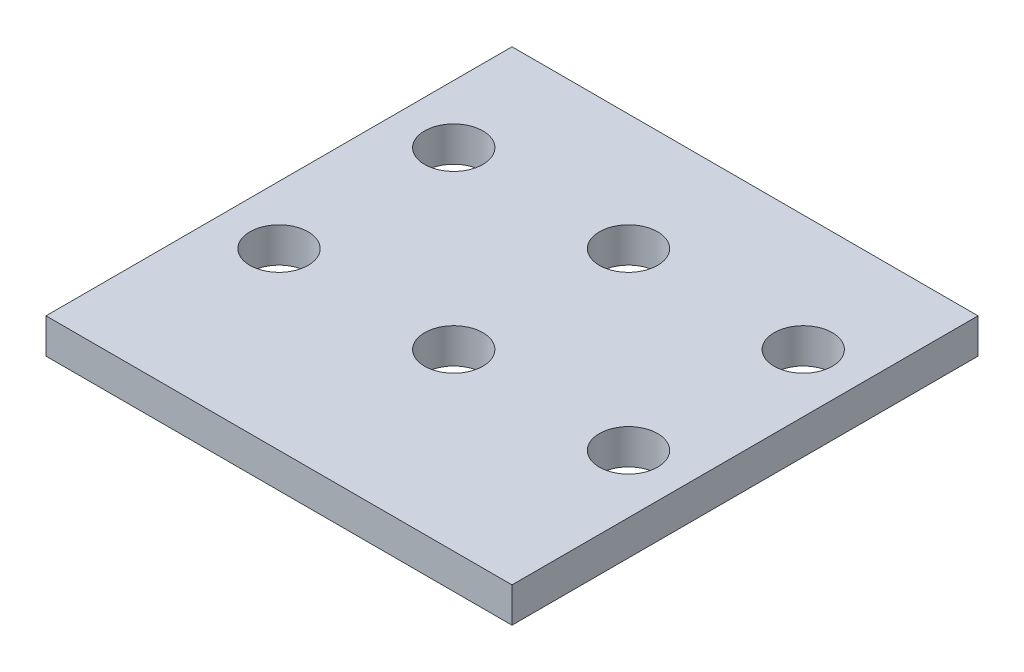
SolidWorks part; units mm, degrees
ref_plane "Front Plane" through (0, 0, 0) normal (0, 0, 1) x (1, 0, 0)
ref_plane "Top Plane" through (0, 0, 0) normal (0, 1, 0) x (1, 0, 0)
ref_plane "Right Plane" through (0, 0, 0) normal (1, 0, 0) x (0, 0, -1)
sketch "Sketch1" plane through (0, 0, 0) normal (0, 1, 0) x (1, 0, 0)
  line L1 (-25.4, -25.4) -> (25.4, -25.4)
  line L2 (-25.4, -25.4) -> (-25.4, 25.4)
  line L3 (-25.4, 25.4) -> (25.4, 25.4)
  line L4 (25.4, -25.4) -> (25.4, 25.4)
  line L5 (-25.4, -25.4) -> (25.4, 25.4) construction
  line L6 (-25.4, 25.4) -> (25.4, -25.4) construction
  point P0 (0, 0)
  dimension "D1" = 50.8
  dimension "D2" = 50.8
extrude "Boss-Extrude1" add sketch "Sketch1" along normal blind 3.81
sketch "Sketch2" plane through (0, 3.81, 0) normal (0, 1, 0) x (1, 0, 0)
  line L0 (-25.4, 25.4) -> (-25.4, -25.4) construction
  line L2 (-25.4, -25.4) -> (25.4, -25.4) construction
  circle A0 centre (-19.05, -6.35) radius 3.175
  dimension "D1" = 6.35
  dimension "D2" = 6.35
  dimension "D3" = 19.05
extrude "Cut-Extrude1" cut sketch "Sketch2" against normal through all
pattern_linear "LPattern1" count 2 spacing 19.05 along (0, 0, -1) count 3 spacing 19.05 along (1, 0, 0) of "Cut-Extrude1"
